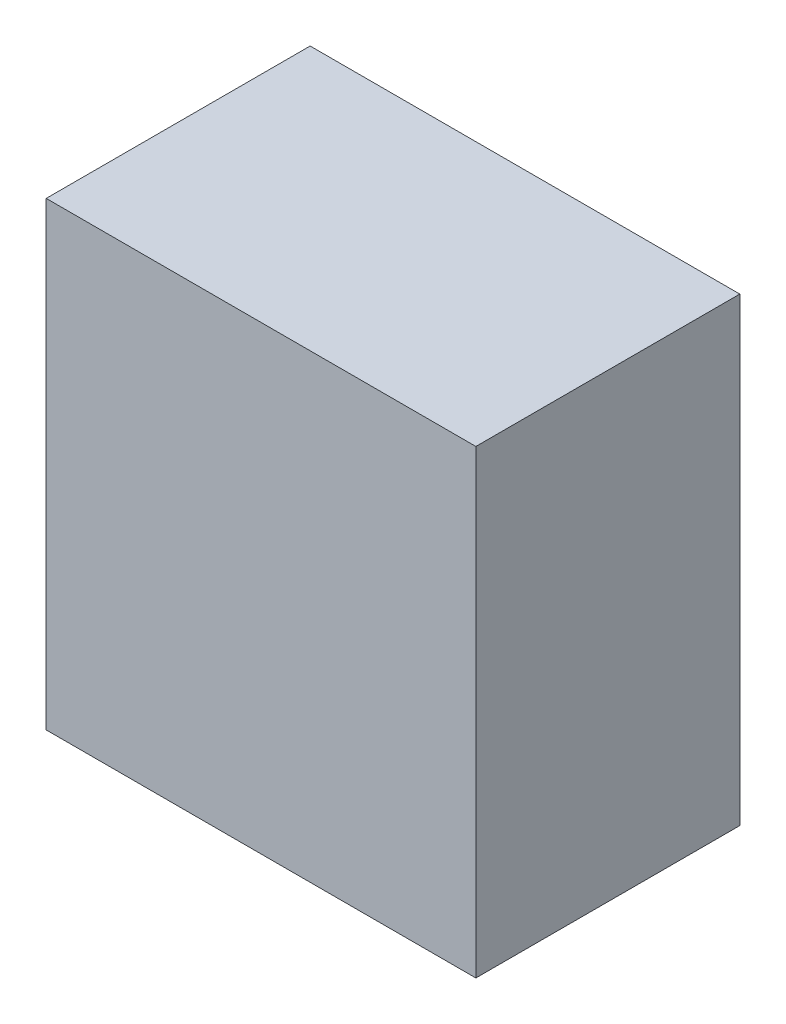
SolidWorks part; units mm, degrees
material "Цинк AC41A сплав, литой"
ref_plane "Спереди" through (0, 0, 0) normal (0, 0, 1) x (1, 0, 0)
ref_plane "Сверху" through (0, 0, 0) normal (0, 1, 0) x (1, 0, 0)
ref_plane "Справа" through (0, 0, 0) normal (1, 0, 0) x (0, 0, -1)
sketch "Эскиз1" plane through (0, 0, 0) normal (1, 0, 0) x (0, 0, -1)
  line L1 (0, 0) -> (86, 0)
  line L2 (0, 0) -> (0, 150)
  line L3 (0, 150) -> (86, 150)
  line L4 (86, 0) -> (86, 150)
  point P5 (80, 6)
  point P6 (16, 6)
  point P7 (6, 120)
  point P8 (80, 144)
  point P9 (0, 0)
  point P10 (0, 0)
  point P11 (0, 0)
  point P12 (0, 0)
  dimension "D1" = 86
  dimension "D2" = 150
  dimension "D3" = 16
  dimension "D4" = 64
  dimension "D5" = 6
  dimension "D6" = 6
  dimension "D7" = 120
  dimension "D8" = 138
  dimension "D9" = 6
  dimension "D10" = 74
extrude "Бобышка-Вытянуть1" add sketch "Эскиз1" along normal blind 140
hole_wizard "Диаметр отверстия Ø3.0 (3)1" positions "Эскиз2" profile "Эскиз3" hole size "Ø3.0" standard "Ansi Metric"
sketch "Эскиз2" plane through (0, 0, 0) normal (-1, 0, 0) x (0, 0, 1)
  point P0 (-80, 144)
  point P3 (-6, 120)
  point P6 (-16, 6)
  point P9 (-80, 6)
sketch "Эскиз3" plane through (0, 144, -80) normal (0, 1, 0) x (0, 0, 1)
  line L0 (0, 0) -> (0, 5.9013)
  line L1 (0, 5.9013) -> (1.5, 5)
  line L2 (1.5, 5) -> (1.5, 0)
  line L5 (1.5, 0) -> (0, 0)
  line L10 (0, 5.9013) -> (-1.5, 5) construction
  line L11 (0, -6.35) -> (0, 107.95) construction
  dimension "Диаметр отверстия" = 3
  dimension "Глубина отверстия" = 5
  dimension "Угол заточки сверла" = 118
